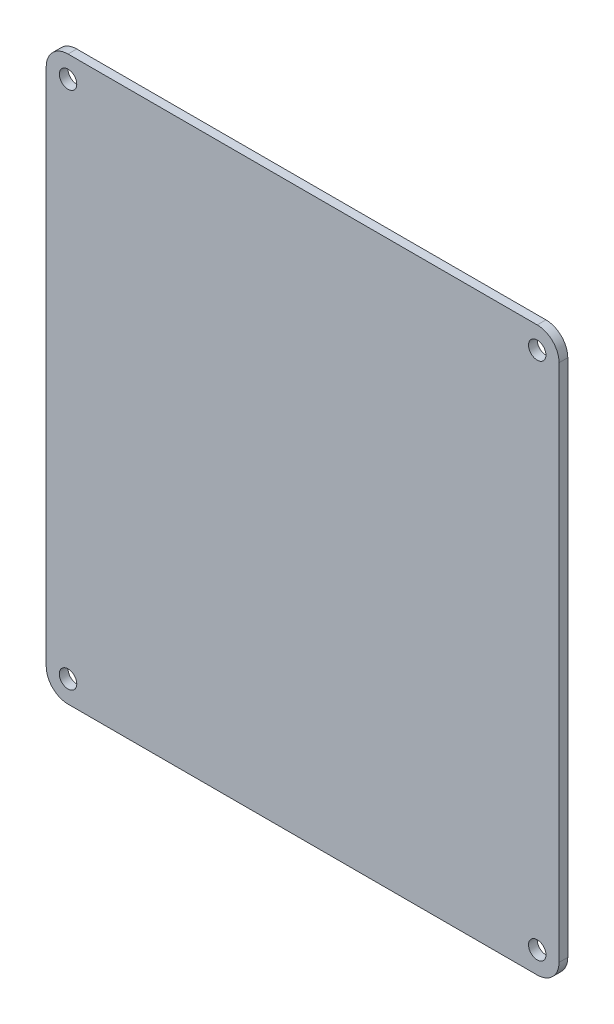
SolidWorks part; units mm, degrees
ref_plane "Front Plane" through (0, 0, 0) normal (0, 0, 1) x (1, 0, 0)
ref_plane "Top Plane" through (0, 0, 0) normal (0, 1, 0) x (1, 0, 0)
ref_plane "Right Plane" through (0, 0, 0) normal (1, 0, 0) x (0, 0, -1)
sketch "Sketch1" plane through (0, 0, 0) normal (0, 0, 1) x (1, 0, 0)
  line L0 (64, -136.5) -> (64, -77.5) construction
  line L1 (69, -42.5) -> (176.5, -42.5)
  line L2 (64, -47.5) -> (64, -166.5)
  line L3 (69, -171.5) -> (176.5, -171.5)
  line L4 (181.5, -47.5) -> (181.5, -166.5)
  line L5 (146.5, -171.5) -> (99, -171.5) construction
  line L6 (181.5, -77.5) -> (181.5, -136.5) construction
  line L7 (99, -42.5) -> (146.5, -42.5) construction
  arc A0 (64, -166.5) -> (69, -171.5) centre (69, -166.5) ccw
  arc A1 (176.5, -171.5) -> (181.5, -166.5) centre (176.5, -166.5) ccw
  arc A2 (176.5, -42.5) -> (181.5, -47.5) centre (176.5, -47.5) cw
  arc A3 (69, -42.5) -> (64, -47.5) centre (69, -47.5) ccw
  circle A8 centre (69, -47.5) radius 2
  circle A9 centre (176.5, -47.5) radius 2
  circle A10 centre (69, -166.5) radius 2
  circle A11 centre (176.5, -166.5) radius 2
  dimension "D1" = 0
  dimension "D2" = 0
  dimension "D3" = 0
  dimension "D4" = 0
extrude "Boss-Extrude1" add sketch "Sketch1" along normal blind 2
